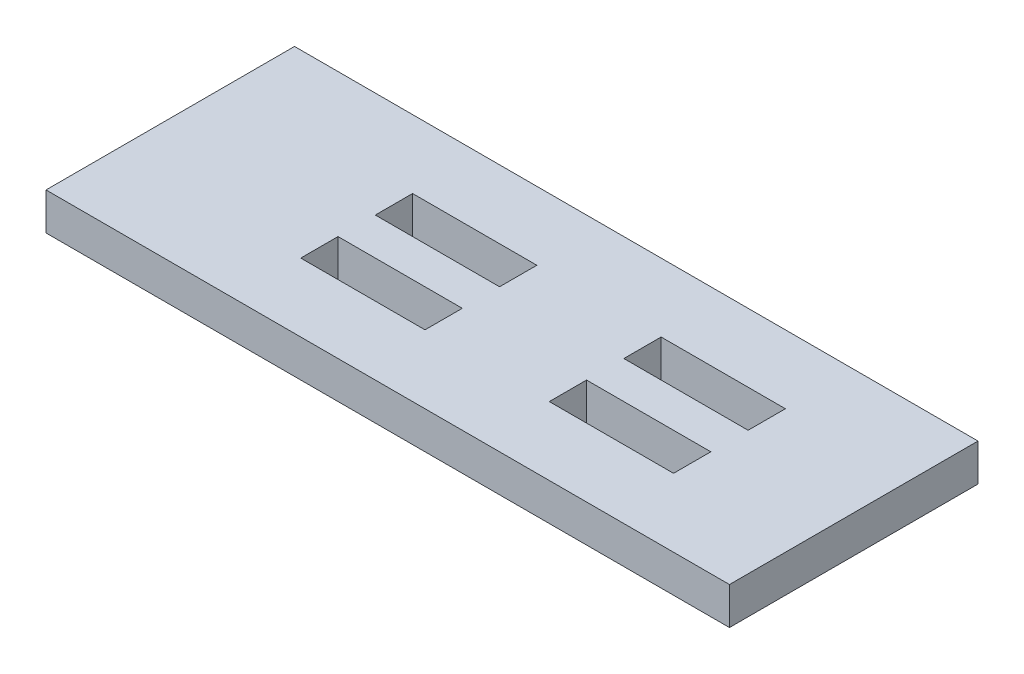
SolidWorks part; units mm, degrees
material "Acrylic (Medium-high impact)"
ref_plane "Front Plane" through (0, 0, 0) normal (0, 0, 1) x (1, 0, 0)
ref_plane "Top Plane" through (0, 0, 0) normal (0, 1, 0) x (1, 0, 0)
ref_plane "Right Plane" through (0, 0, 0) normal (1, 0, 0) x (0, 0, -1)
sketch "Sketch1" plane through (0, 0, 0) normal (0, 1, 0) x (1, 0, 0)
  line L1 (0, 0) -> (-55, 0)
  line L2 (0, 0) -> (0, 20)
  line L3 (0, 20) -> (-55, 20)
  line L4 (-55, 0) -> (-55, 20)
  dimension "D1" = 55
  dimension "D2" = 20
extrude "Boss-Extrude1" add sketch "Sketch1" along normal blind 3
sketch "Sketch2" plane through (0, 3, 0) normal (0, 1, 0) x (1, 0, 0)
  line L0 (0, 0) -> (0, 20) construction
  line L1 (-20, 14.5) -> (-10, 14.5)
  line L2 (-20, 14.5) -> (-20, 11.5)
  line L3 (-20, 11.5) -> (-10, 11.5)
  line L4 (-10, 14.5) -> (-10, 11.5)
  line L5 (0, 20) -> (-55, 20) construction
  line L7 (-30, 11.5) -> (-40, 11.5)
  line L8 (-30, 11.5) -> (-30, 14.5)
  line L9 (-30, 14.5) -> (-40, 14.5)
  line L10 (-40, 11.5) -> (-40, 14.5)
  line L11 (-10, 5.5) -> (-20, 5.5)
  line L12 (-10, 5.5) -> (-10, 8.5)
  line L13 (-10, 8.5) -> (-20, 8.5)
  line L14 (-20, 5.5) -> (-20, 8.5)
  line L15 (-30, 5.5) -> (-40, 5.5)
  line L16 (-30, 5.5) -> (-30, 8.5)
  line L17 (-30, 8.5) -> (-40, 8.5)
  line L18 (-40, 5.5) -> (-40, 8.5)
  dimension "D1" = 10
  dimension "D2" = 10
  dimension "D3" = 5.5
  dimension "D4" = 3
  dimension "D5" = 10
  dimension "D6" = 3
  dimension "D7" = 5.5
  dimension "D8" = 10
  dimension "D9" = 10
  dimension "D10" = 3
  dimension "D11" = 3
  dimension "D12" = 10
  dimension "D13" = 10
  dimension "D14" = 3
  dimension "D15" = 3
  dimension "D16" = 10
extrude "Cut-Extrude1" cut sketch "Sketch2" against normal blind 3
